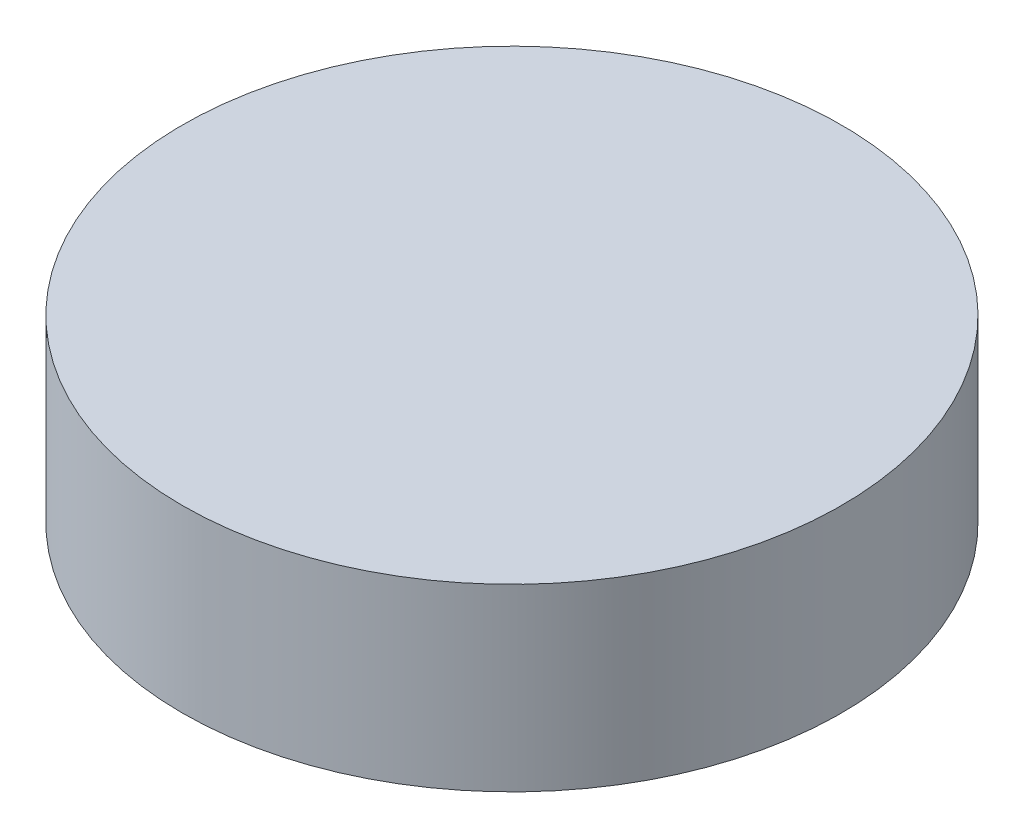
SolidWorks part; units mm, degrees
ref_plane "Front Plane" through (0, 0, 0) normal (0, 0, 1) x (1, 0, 0)
ref_plane "Top Plane" through (0, 0, 0) normal (0, 1, 0) x (1, 0, 0)
ref_plane "Right Plane" through (0, 0, 0) normal (1, 0, 0) x (0, 0, -1)
sketch "Sketch1" plane through (0, 0, 0) normal (0, 1, 0) x (1, 0, 0)
  circle A0 centre (0, 0) radius 27.5
  dimension "D1" = 55
extrude "Boss-Extrude1" add sketch "Sketch1" along normal blind 15
